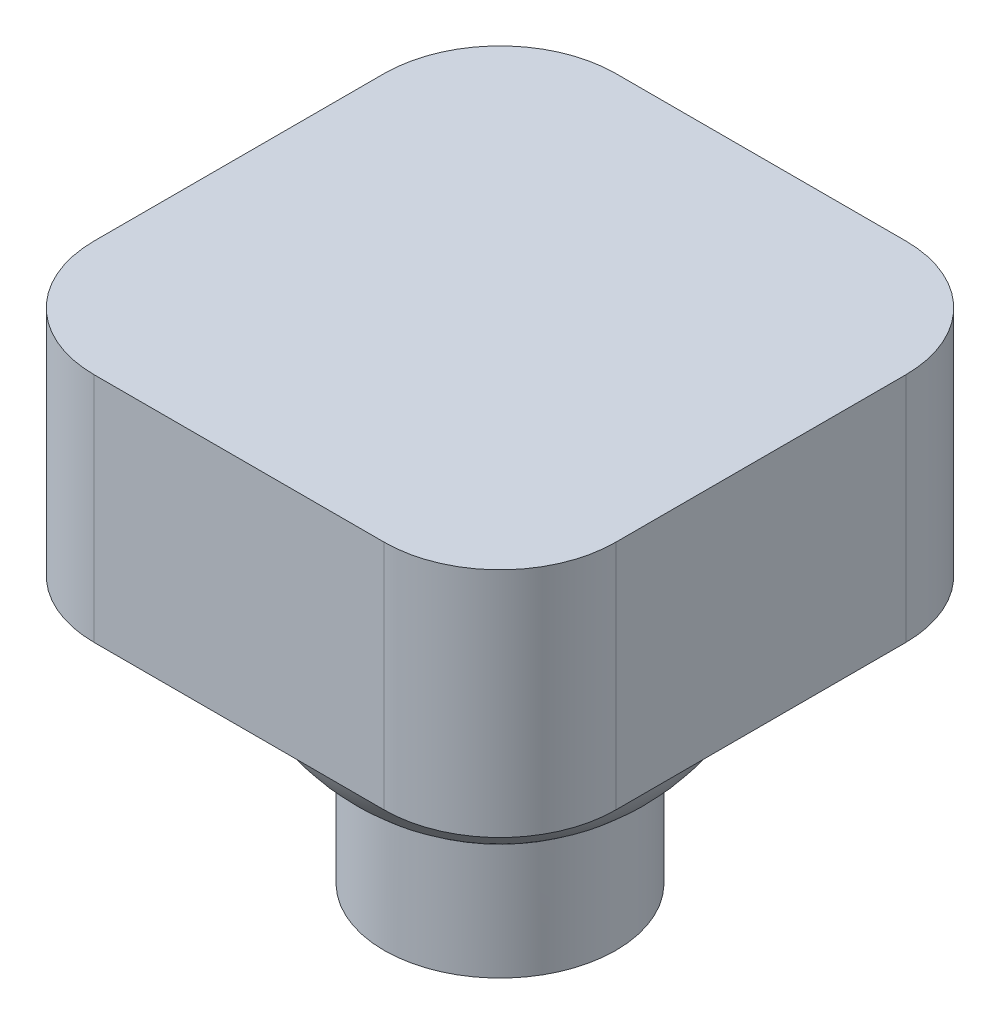
SolidWorks part; units mm, degrees
material "AISI 4340 Steel, normalized"
ref_plane "Front Plane" through (0, 0, 0) normal (0, 0, 1) x (1, 0, 0)
ref_plane "Top Plane" through (0, 0, 0) normal (0, 1, 0) x (1, 0, 0)
ref_plane "Right Plane" through (0, 0, 0) normal (1, 0, 0) x (0, 0, -1)
sketch "Sketch1" plane through (0, 0, 0) normal (0, 1, 0) x (1, 0, 0)
  circle A0 centre (0, 0) radius 25.4
  dimension "D1" = 50.8
extrude "Boss-Extrude1" add sketch "Sketch1" along normal blind 25.4
sketch "Sketch2" plane through (0, 0, 0) normal (0, 0, 1) x (1, 0, 0)
  line L0 (0, 145.4603) -> (0, 25.4)
  line L1 (25.4, 25.4) -> (-25.4, 25.4) construction
  line L2 (0, 25.4) -> (25.4, 25.4)
  line L3 (25.4, 0) -> (25.4, 25.4) construction
  circle A0 centre (0, 61.878) radius 44.45
  dimension "D1" = 88.9
revolve "Revolve1" add sketch "Sketch2" angle 360 about L0
ref_plane "Plane1" through (0, 58.42, 0) normal (0, 1, 0) x (1, 0, 0)
sketch "Sketch3" plane through (0, 58.42, 0) normal (0, 1, 0) x (1, 0, 0)
  line L1 (-57.15, 57.15) -> (57.15, 57.15)
  line L2 (-57.15, 57.15) -> (-57.15, -57.15)
  line L3 (-57.15, -57.15) -> (57.15, -57.15)
  line L4 (57.15, 57.15) -> (57.15, -57.15)
  circle A0 centre (0, 0) radius 44.45 construction
  point P5 (0, -57.15)
  point P7 (57.15, 0)
  point P10 (0, 44.45)
  point P11 (44.45, 0)
  dimension "D1" = 12.7
  dimension "D2" = 12.7
extrude "Boss-Extrude2" add sketch "Sketch3" along normal blind 50.8
fillet "Fillet1" radius 25.4 4 edges at (-57.15, 83.82, -57.15) (57.15, 83.82, -57.15) (57.15, 83.82, 57.15) (-57.15, 83.82, 57.15)
sketch "Sketch4" plane through (0, 109.22, 0) normal (0, 1, 0) x (1, 0, 0)
  line L0 (57.15, 0) -> (-57.15, 0) construction
  line L1 (57.15, -31.75) -> (57.15, 31.75) construction
  line L2 (-57.15, 31.75) -> (-57.15, -31.75) construction
  line L3 (0, 57.15) -> (0, -57.15) construction
  line L4 (31.75, 57.15) -> (-31.75, 57.15) construction
  line L5 (-31.75, -57.15) -> (31.75, -57.15) construction
